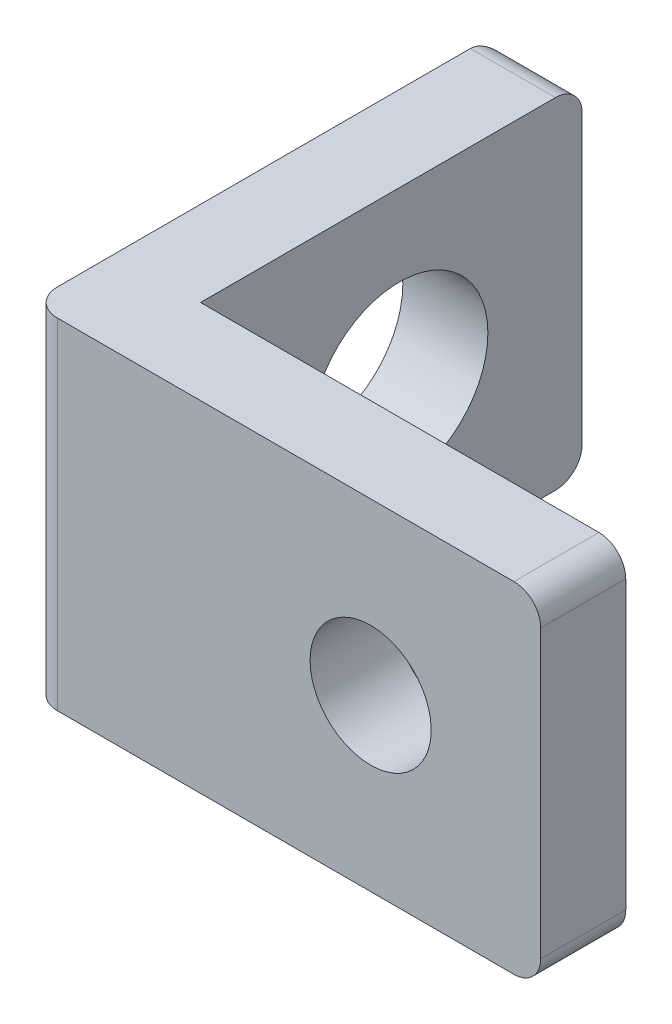
SolidWorks part; units mm, degrees
ref_plane "Front Plane" through (0, 0, 0) normal (0, 0, 1) x (1, 0, 0)
ref_plane "Top Plane" through (0, 0, 0) normal (0, 1, 0) x (1, 0, 0)
ref_plane "Right Plane" through (0, 0, 0) normal (1, 0, 0) x (0, 0, -1)
sketch "Sketch1" plane through (0, 0, 0) normal (0, 1, 0) x (1, 0, 0)
  line L1 (0, 0) -> (9.525, 0)
  line L2 (0, 0) -> (0, 8.7122)
  line L3 (0, 8.7122) -> (9.525, 8.7122)
  line L4 (9.525, 0) -> (9.525, 8.7122)
  line L5 (9.525, 8.7122) -> (1.5875, 8.7122)
  line L6 (9.525, 8.7122) -> (9.525, 1.5875)
  line L7 (9.525, 1.5875) -> (1.5875, 1.5875)
  line L8 (1.5875, 8.7122) -> (1.5875, 1.5875)
  dimension "D1" = 9.525
  dimension "D2" = 8.7122
  dimension "D3" = 1.5875
  dimension "D4" = 1.5875
extrude "Boss-Extrude1" add sketch "Sketch1" along normal blind 6.35 contours L8 L3 L2 L1 L4 L7
sketch "Sketch2" plane through (1.5875, 0, 0) normal (1, 0, 0) x (0, 0, -1)
  line L0 (1.5875, 6.35) -> (1.5875, 0) construction
  circle A0 centre (5.3, 3.175) radius 1.651
  dimension "D1" = 3.302
  dimension "D2" = 3.7125
extrude "Cut-Extrude1" cut sketch "Sketch2" against normal up to next
sketch "Sketch4" plane through (0, 0, -1.5875) normal (0, 0, -1) x (-1, 0, 0)
  line L1 (-9.525, 0) -> (-6.35, 0)
  line L2 (-9.525, 0) -> (-9.525, 3.175)
  line L3 (-9.525, 3.175) -> (-6.35, 3.175)
  line L4 (-6.35, 0) -> (-6.35, 3.175)
  dimension "D1" = 3.175
  dimension "D2" = 3.175
hole_wizard "#4-40 Tapped Hole2" positions "3DSketch2" profile "Sketch5" tap size "#4-40" standard "ANSI Inch" end condition through all
sketch3d "3DSketch2"
  point P0 (6.35, 3.175, -1.5875)
sketch "Sketch5" plane through (6.35, 3.175, -1.5875) normal (1, 0, 0) x (0, 1, 0)
  line L0 (0, 0) -> (0, 1.5875)
  line L1 (0, 1.5875) -> (1.1303, 1.5875)
  line L2 (1.1303, 1.5875) -> (1.1303, 0)
  line L5 (1.1303, 0) -> (0, 0)
  line L11 (0, -6.35) -> (0, 107.95) construction
  dimension "Thru Tap Drill Dia." = 2.2606
  dimension "Thru Tap Drill Depth" = 1.5875
cosmetic thread "Hole Thread2" parameters "D2"=2.8448
fillet "Fillet1" radius 0.5 6 edges at (0.7938, 0, -8.7122) (0.7938, 6.35, -8.7122) (9.525, 0, -0.7938) (9.525, 6.35, -0.7938) (0, 3.175, 0) (0, 3.175, -8.7122)
equation "\"SheetThickness\"= 0.0625in"
equation "\"D3@Sketch1\"=\"SheetThickness\""
equation "\"D4@Sketch1\"=\"SheetThickness\""
equation "\"BracketWidth\"= 0.25in"
equation "\"D1@Boss-Extrude1\"=\"BracketWidth\""
equation "\"HoleOffset\"= 0.125in"
equation "\"D1@Sketch4\"=\"HoleOffset\""
equation "\"D2@Sketch4\"=\"HoleOffset\""
